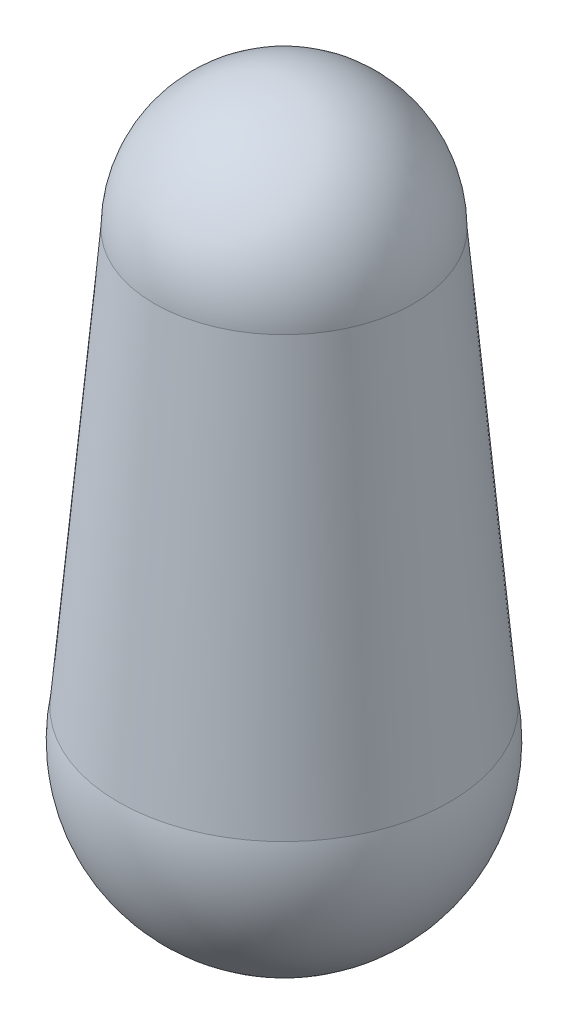
SolidWorks part; units mm, degrees
material "1060 Alloy"
ref_plane "Front Plane" through (0, 0, 0) normal (0, 0, 1) x (1, 0, 0)
ref_plane "Top Plane" through (0, 0, 0) normal (0, 1, 0) x (1, 0, 0)
ref_plane "Right Plane" through (0, 0, 0) normal (1, 0, 0) x (0, 0, -1)
sketch "Sketch1" plane through (0, 0, 0) normal (0, 1, 0) x (1, 0, 0)
  line L0 (0, 3.8) -> (0, -3.8) construction
  line L1 (0, 3.8) -> (0, -3.8)
  arc A0 (0, -3.8) -> (0, 3.8) centre (0, 0) ccw
  dimension "D1" = 7.6
revolve "Revolve1" add sketch "Sketch1" angle 360 about L0
sketch "Sketch2" plane through (0, 0, 0) normal (0, 1, 0) x (1, 0, 0)
  circle A0 centre (0, 0) radius 3.8
  circle A1 centre (0, 0) radius 3.8 construction
extrude "Boss-Extrude1" add sketch "Sketch2" along normal blind 10 draft 5
sketch "Sketch3" plane through (0, 10, 0) normal (0, 1, 0) x (1, 0, 0)
  line L0 (0, 2.9251) -> (0, -2.9251) construction
  line L1 (0, 2.9251) -> (0, -2.9251)
  arc A0 (0, -2.9251) -> (0, 2.9251) centre (0, 0) ccw
  circle A1 centre (0, 0) radius 2.9251 construction
revolve "Revolve2" add sketch "Sketch3" angle 360 about L0
